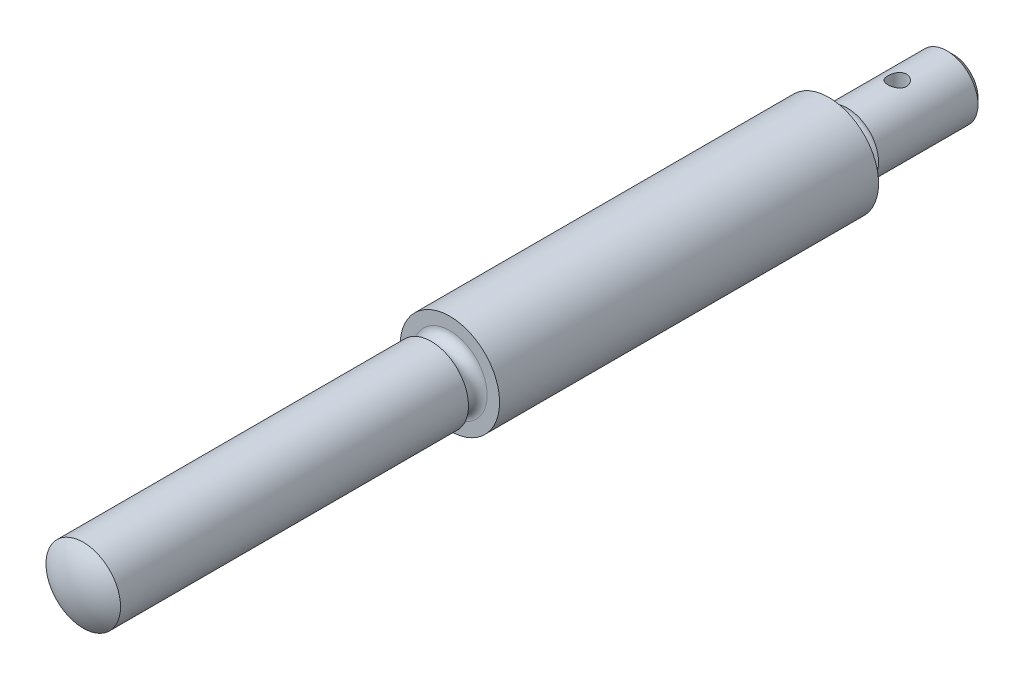
SolidWorks part; units mm, degrees
ref_plane "前基準面" through (0, 0, 0) normal (0, 0, 1) x (1, 0, 0)
ref_plane "上基準面" through (0, 0, 0) normal (0, 1, 0) x (1, 0, 0)
ref_plane "右基準面" through (0, 0, 0) normal (1, 0, 0) x (0, 0, -1)
sketch "草圖1" plane through (0, 0, 0) normal (1, 0, 0) x (0, 0, -1)
  line L0 (0, 0) -> (207.0095, 0) construction
  line L1 (2, 6) -> (58, 6)
  line L2 (122, 8) -> (122, 5)
  line L3 (61, 6) -> (61, 8)
  line L4 (61, 8) -> (122, 8)
  line L5 (125, 5) -> (142, 5)
  line L7 (142, 5) -> (142, 0)
  line L8 (0, 0) -> (142, 0)
  arc A0 (2, 6) -> (0, 0) centre (10, 0) ccw
  arc A1 (58, 6) -> (61, 6) centre (59.5, 6) ccw
  arc A2 (122, 5) -> (125, 5) centre (123.5, 5) ccw
  dimension "D3" = 9
  dimension "D4" = 1.5
  dimension "D9" = 1.5
  dimension "D11" = 142
  dimension "D1" = 2
  dimension "D2" = 12
  dimension "D5" = 61
  dimension "D7" = 10
  dimension "D10" = 20
  dimension "D12" = 16
revolve "旋轉1" add sketch "草圖1" angle 360 about L0
cosmetic thread "裝飾螺紋線1" parameters "D2"=10.2
cosmetic thread "裝飾螺紋線2" parameters "D2"=14
sketch "草圖2" plane through (0, 0, 0) normal (0, 1, 0) x (1, 0, 0)
  line L0 (8, 122) -> (-8, 122) construction
  line L1 (0, 133) -> (0, 0) construction
  circle A0 centre (0, 133) radius 1.5
  dimension "D2" = 3
  dimension "D1" = 11
extrude "除料-伸長1" cut sketch "草圖2" against normal mid plane 20
chamfer "導角1" distance 1 angle 45 1 edges at (5, 0, -142)
